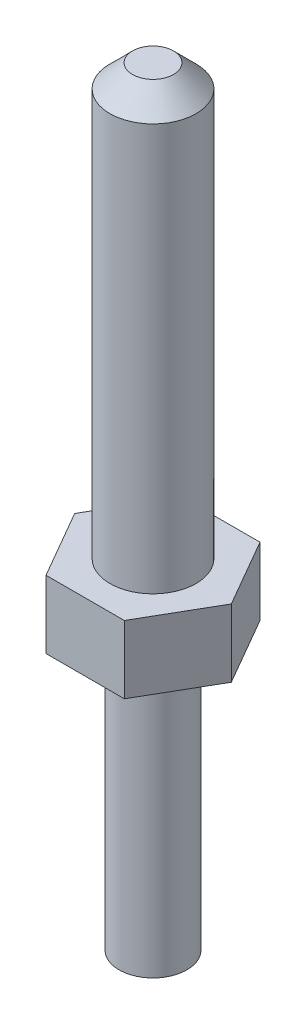
SolidWorks part; units mm, degrees
ref_plane "Front Plane" through (0, 0, 0) normal (0, 0, 1) x (1, 0, 0)
ref_plane "Top Plane" through (0, 0, 0) normal (0, 1, 0) x (1, 0, 0)
ref_plane "Right Plane" through (0, 0, 0) normal (1, 0, 0) x (0, 0, -1)
sketch "Sketch1" plane through (0, 0, 0) normal (0, 0, 1) x (1, 0, 0)
  line L0 (0, 0) -> (0, 12312.5944) construction
  line L1 (0, 34) -> (-1.905, 34)
  line L2 (-1.905, 34) -> (-1.905, 15)
  line L3 (-1.905, 15) -> (-2.5, 15)
  line L4 (-2.5, 15) -> (-2.5, 12)
  line L5 (-2.5, 12) -> (-1.5, 12)
  line L6 (-1.5, 12) -> (-1.5, 0)
  line L7 (-1.5, 0) -> (0, 0)
  line L8 (0, 34) -> (0, 0)
  dimension "D1" = 3.81
  dimension "D2" = 19
  dimension "D3" = 3
  dimension "D4" = 12
  dimension "D5" = 3
  dimension "D6" = 1
revolve "Revolve1" add sketch "Sketch1" angle 360 about L0
sketch "Sketch2" plane through (0, 15, 0) normal (0, 1, 0) x (1, 0, 0)
  line L0 (-3.2228, 0) -> (49996.7772, 0) construction
  line L1 (-3.4641, 0) -> (-1.7321, -3)
  line L2 (-1.7321, -3) -> (1.7321, -3)
  line L3 (1.7321, -3) -> (3.4641, 0)
  line L4 (3.4641, 0) -> (1.7321, 3)
  line L5 (1.7321, 3) -> (-1.7321, 3)
  line L6 (-1.7321, 3) -> (-3.4641, 0)
  circle A0 centre (0, 0) radius 3 construction
  dimension "D1" = 6
extrude "Boss-Extrude1" add sketch "Sketch2" against normal up to surface (3 mm away) up to face at (0, 12, -1.5)
chamfer "Chamfer1" distance 1 angle 45 1 edges at (0, 34, -1.905)
